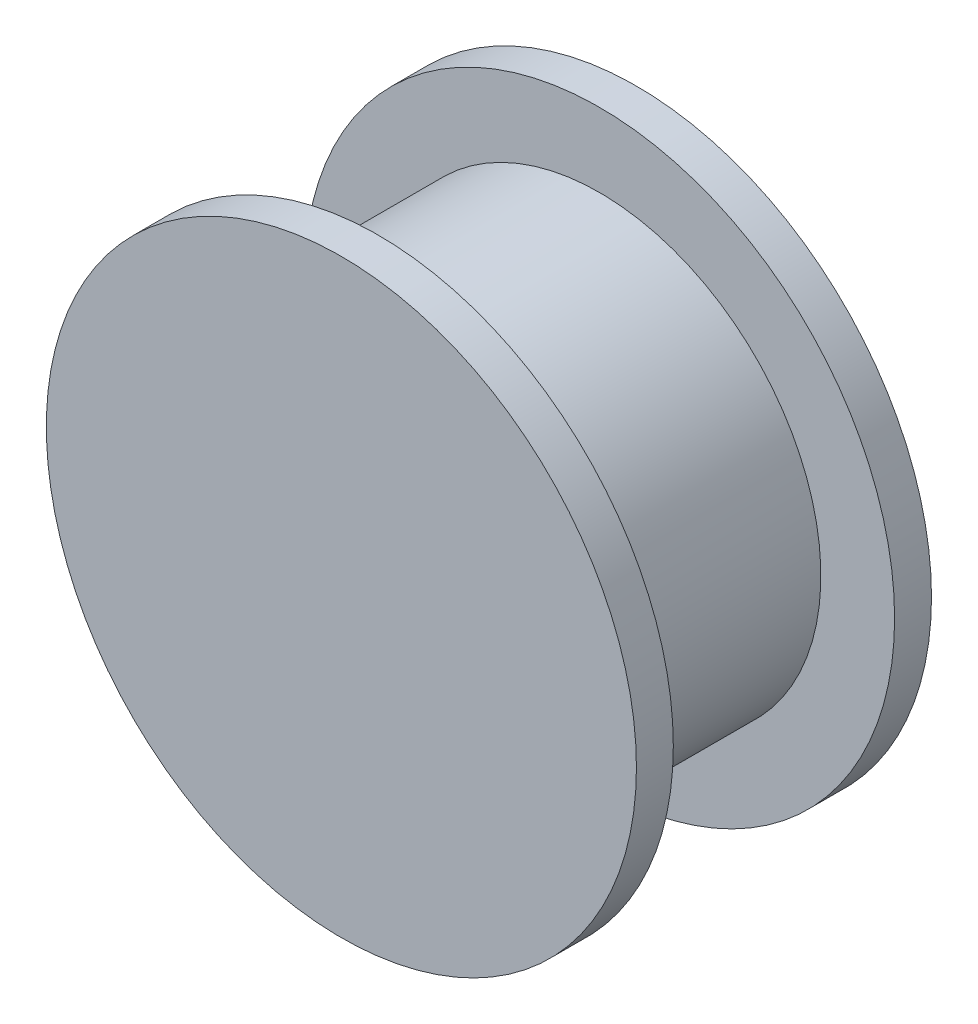
SolidWorks part; units mm, degrees
ref_plane "Front Plane" through (0, 0, 0) normal (0, 0, 1) x (1, 0, 0)
ref_plane "Top Plane" through (0, 0, 0) normal (0, 1, 0) x (1, 0, 0)
ref_plane "Right Plane" through (0, 0, 0) normal (1, 0, 0) x (0, 0, -1)
sketch "Sketch1" plane through (0, 0, 0) normal (0, 0, 1) x (1, 0, 0)
  circle A0 centre (0, 0) radius 25.4
  dimension "D1" = 50.8
extrude "Boss-Extrude1" add sketch "Sketch1" along normal blind 3.175
sketch "Sketch2" plane through (0, 0, 3.175) normal (0, 0, 1) x (1, 0, 0)
  circle A0 centre (0, 0) radius 19.05
  dimension "D1" = 38.1
extrude "Boss-Extrude2" add sketch "Sketch2" along normal blind 19.05
sketch "Sketch3" plane through (0, 0, 22.225) normal (0, 0, 1) x (1, 0, 0)
  circle A0 centre (0, 0) radius 25.4
  dimension "D1" = 50.8
extrude "Boss-Extrude3" add sketch "Sketch3" along normal blind 3.175
